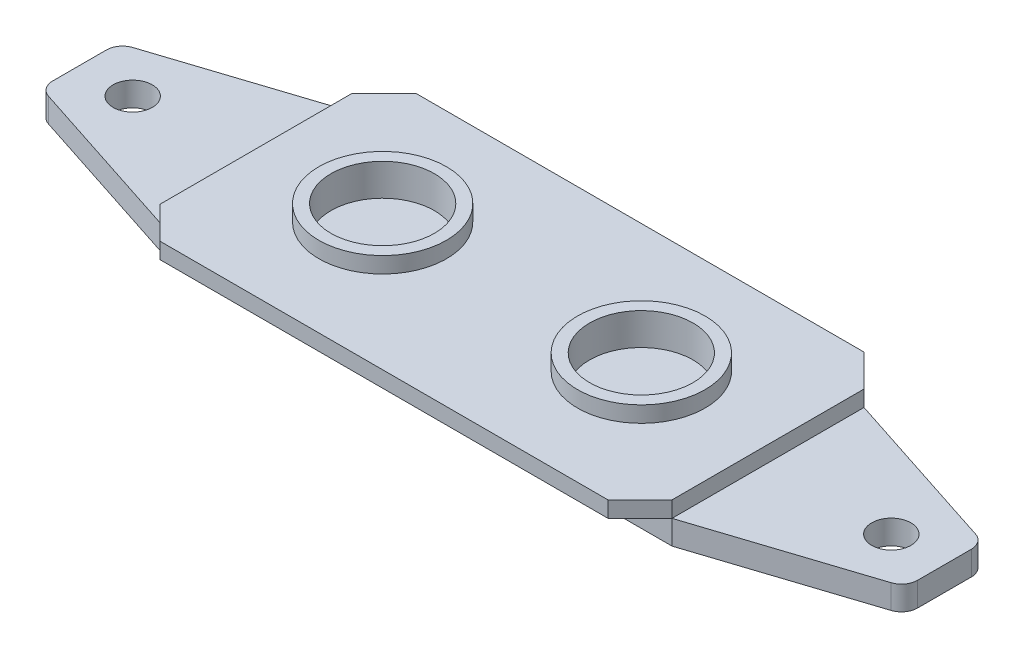
SolidWorks part; units mm, degrees
ref_plane "Front Plane" through (0, 0, 0) normal (0, 0, 1) x (1, 0, 0)
ref_plane "Top Plane" through (0, 0, 0) normal (0, 1, 0) x (1, 0, 0)
ref_plane "Right Plane" through (0, 0, 0) normal (1, 0, 0) x (0, 0, -1)
sketch "Sketch4" plane through (0, 0, 0) normal (0, 1, 0) x (1, 0, 0)
  line L0 (0, 44.45) -> (6.35, 50.8)
  line L1 (6.35, 0) -> (95.25, 0)
  line L2 (0, 6.35) -> (0, 44.45)
  line L3 (6.35, 50.8) -> (95.25, 50.8)
  line L4 (101.6, 6.35) -> (101.6, 44.45)
  line L5 (95.25, 50.8) -> (101.6, 44.45)
  line L6 (95.25, 0) -> (101.6, 6.35)
  line L7 (0, 6.35) -> (6.35, 0)
  point P0 (0, 0)
  point P1 (101.6, 50.8)
  point P2 (0, 50.8)
  point P3 (101.6, 0)
  dimension "D1" = 101.6
  dimension "D2" = 50.8
  dimension "D5" = 6.35
  dimension "D6" = 6.35
  dimension "D7" = 6.35
  dimension "D8" = 6.35
extrude "Extrude1" add sketch "Sketch4" against normal blind 3.175
sketch "Sketch5" plane through (0, 0, 0) normal (0, 1, 0) x (1, 0, 0)
  line L0 (50.8, 0) -> (50.8, 50.8) construction
  line L3 (6.35, 0) -> (95.25, 0) construction
  line L4 (95.25, 50.8) -> (6.35, 50.8) construction
  circle A0 centre (25.1403, 25.4) radius 12.6588
  circle A1 centre (25.1403, 25.4) radius 10.2639
  circle A2 centre (76.4597, 25.4) radius 10.2639
  circle A3 centre (76.4597, 25.4) radius 12.6588
extrude "Extrude2" add sketch "Sketch5" along normal blind 3.175
ref_plane "Plane2" through (0, -3.175, 0) normal (0, 1, 0) x (-1, 0, 0)
sketch "Sketch7" plane through (0, 0, 0) normal (0, 1, 0) x (1, 0, 0)
  circle A0 centre (25.1403, 25.4) radius 10.2639 construction
  circle A1 centre (25.1403, 25.4) radius 10.2639
  circle A2 centre (76.4597, 25.4) radius 10.2639 construction
  circle A3 centre (76.4597, 25.4) radius 10.2639
extrude "Extrude3" cut sketch "Sketch7" against normal through all
sketch "Sketch8" plane through (0, -3.175, 0) normal (0, 1, 0) x (-1, 0, 0)
  line L1 (-101.6, -6.35) -> (0, -6.35)
  line L2 (-101.6, -6.35) -> (-101.6, -44.45)
  line L3 (-101.6, -44.45) -> (0, -44.45)
  line L4 (0, -6.35) -> (0, -44.45)
  line L5 (-136.6061, -20.053) -> (-136.6061, -30.747)
  line L6 (-134.4141, -17.034) -> (-101.6, -6.35)
  line L7 (-134.4141, -33.766) -> (-101.6, -44.45)
  line L8 (-50.8, 0) -> (-50.8, -59.3142) construction
  line L9 (32.8141, -33.766) -> (0, -44.45)
  line L10 (32.8141, -17.034) -> (0, -6.35)
  line L11 (35.0061, -20.053) -> (35.0061, -30.747)
  line L12 (0, -6.35) -> (0, -44.45)
  arc A0 (-134.4141, -17.034) -> (-136.6061, -20.053) centre (-133.4311, -20.053) ccw
  arc A1 (-134.4141, -33.766) -> (-136.6061, -30.747) centre (-133.4311, -30.747) cw
  circle A2 centre (-126.0685, -25.4) radius 3.8889
  circle A3 centre (24.4685, -25.4) radius 3.8889
  arc A4 (32.8141, -33.766) -> (35.0061, -30.747) centre (31.8311, -30.747) ccw
  arc A5 (32.8141, -17.034) -> (35.0061, -20.053) centre (31.8311, -20.053) cw
  point P12 (-136.6061, -17.7477)
  point P15 (-136.6061, -33.0523)
  point P31 (35.0061, -33.0523)
  point P32 (35.0061, -17.7477)
extrude "Extrude4" add sketch "Sketch8" against normal blind 4.7752 contours A1 L7 L2 L6 A0 L5 A2 | L8 L1 L2 L3 | L1 L8 L3 L4 | A5 L10 L4 L9 A4 L11 A3
